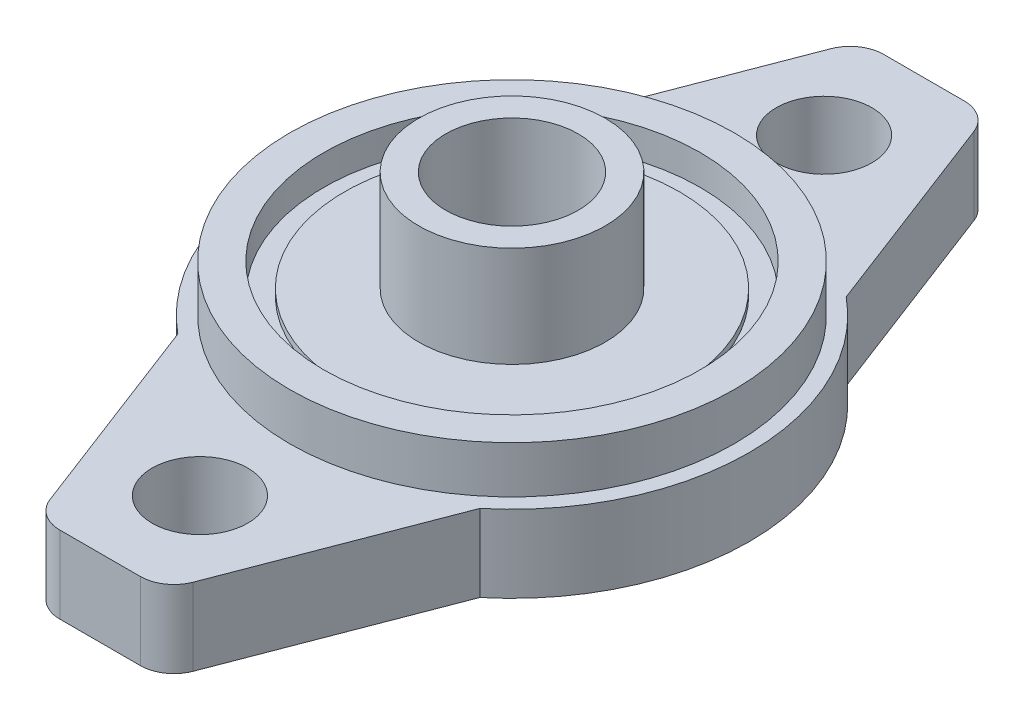
SolidWorks part; units mm, degrees
material "201 Annealed Stainless Steel (SS)"
ref_plane "Front Plane" through (0, 0, 0) normal (0, 0, 1) x (1, 0, 0)
ref_plane "Top Plane" through (0, 0, 0) normal (0, 1, 0) x (1, 0, 0)
ref_plane "Right Plane" through (0, 0, 0) normal (1, 0, 0) x (0, 0, -1)
sketch "Sketch1" plane through (0, 0, 0) normal (0, 1, 0) x (1, 0, 0)
  circle A0 centre (0, 0) radius 5.0165
  circle A1 centre (0, 0) radius 7.0612
  dimension "D1" = 10.033
  dimension "D2" = 14.1224
extrude "Boss-Extrude1" add sketch "Sketch1" along normal blind 15.24
sketch "Sketch2" plane through (0, 0, 0) normal (0, 1, 0) x (1, 0, 0)
  circle A0 centre (0, 0) radius 12.6683
  circle A1 centre (0, 0) radius 7.0612 construction
  circle A2 centre (0, 0) radius 7.0612
  dimension "D1" = 25.3365
extrude "Boss-Extrude2" add sketch "Sketch2" along normal blind 7.62
sketch "Sketch3" plane through (0, 0, 0) normal (0, -1, 0) x (1, 0, 0)
  circle A0 centre (0, 0) radius 14.2494
  circle A1 centre (0, 0) radius 12.6683 construction
  circle A2 centre (0, 0) radius 12.6683
  dimension "D1" = 28.4988
extrude "Boss-Extrude3" add sketch "Sketch3" against normal blind 7.112
sketch "Sketch4" plane through (0, 0, 0) normal (0, -1, 0) x (1, 0, 0)
  circle A0 centre (0, 0) radius 16.8275
  circle A1 centre (0, 0) radius 14.2494 construction
  circle A2 centre (0, 0) radius 14.2494
  dimension "D1" = 33.655
extrude "Boss-Extrude4" add sketch "Sketch4" against normal blind 9.398
sketch "Sketch5" plane through (0, 0, 0) normal (0, 1, 0) x (1, 0, 0)
  line L0 (11.43, 13.867) -> (5.4197, 29.5476)
  line L1 (3.048, 31.1785) -> (-3.048, 31.1785)
  line L2 (0, 31.1785) -> (0, 17.9705)
  line L3 (-11.43, 13.867) -> (-5.4197, 29.5476)
  line L4 (0, 0) -> (9.7703, 0) construction
  line L5 (-11.43, -13.867) -> (-5.4197, -29.5476)
  line L6 (11.43, -13.867) -> (5.4197, -29.5476)
  line L7 (3.048, -31.1785) -> (-3.048, -31.1785)
  circle A0 centre (0, 0) radius 17.9705
  circle A1 centre (0, 0) radius 16.8275 construction
  circle A2 centre (0, 0) radius 16.8275
  arc A3 (-5.4197, -29.5476) -> (-3.048, -31.1785) centre (-3.048, -28.6385) ccw
  arc A4 (5.4197, -29.5476) -> (3.048, -31.1785) centre (3.048, -28.6385) cw
  arc A5 (5.4197, 29.5476) -> (3.048, 31.1785) centre (3.048, 28.6385) ccw
  arc A6 (-5.4197, 29.5476) -> (-3.048, 31.1785) centre (-3.048, 28.6385) cw
  point P19 (-4.7946, -31.1785)
  point P22 (4.7946, -31.1785)
  point P25 (4.7946, 31.1785)
  point P28 (-4.7946, 31.1785)
  dimension "D1" = 35.941
  dimension "D4" = 2.54
  dimension "D2" = 11.43
  dimension "D3" = 13.208
  dimension "D5" = 6.096
extrude "Boss-Extrude5" add sketch "Sketch5" along normal blind 5.842 contours A0 L0 L1 L2 | A0 L2 L1 L3 | A0 A2 | A0 L5 L7 L6
sketch "Sketch6" plane through (0, 5.842, 0) normal (0, 1, 0) x (1, 0, 0)
  line L0 (0, 0) -> (-28.4768, 0) construction
  circle A0 centre (0, 23.622) radius 3.6195
  circle A1 centre (0, 0) radius 16.8275 construction
  circle A2 centre (0, -23.622) radius 3.6195
  point P7 (0, 0)
  point P8 (0, 0)
  dimension "D1" = 23.622
  dimension "D2" = 7.239
extrude "Cut-Extrude1" cut sketch "Sketch6" against normal up to next
